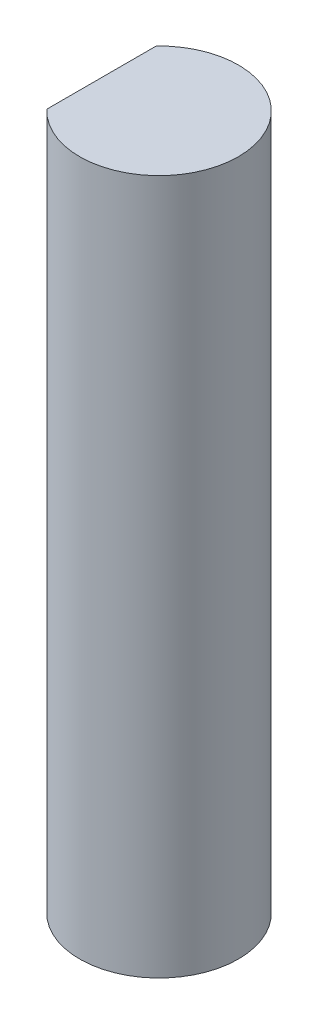
SolidWorks part; units mm, degrees
ref_plane "Front Plane" through (0, 0, 0) normal (0, 0, 1) x (1, 0, 0)
ref_plane "Top Plane" through (0, 0, 0) normal (0, 1, 0) x (1, 0, 0)
ref_plane "Right Plane" through (0, 0, 0) normal (1, 0, 0) x (0, 0, -1)
sketch "Sketch1" plane through (0, 0, 0) normal (0, 1, 0) x (1, 0, 0)
  circle A0 centre (0, 0) radius 4
  dimension "D1" = 8
extrude "Boss-Extrude1" add sketch "Sketch1" along normal blind 35
sketch "Sketch2" plane through (0, 0, 0) normal (0, -1, 0) x (1, 0, 0)
  line L1 (-2.899, 2.8936) -> (-4.6583, 2.8936)
  line L2 (-2.899, 2.8936) -> (-2.899, -3.761)
  line L3 (-2.899, -3.761) -> (-4.6583, -3.761)
  line L4 (-4.6583, 2.8936) -> (-4.6583, -3.761)
extrude "Cut-Extrude1" cut sketch "Sketch2" against normal through all
